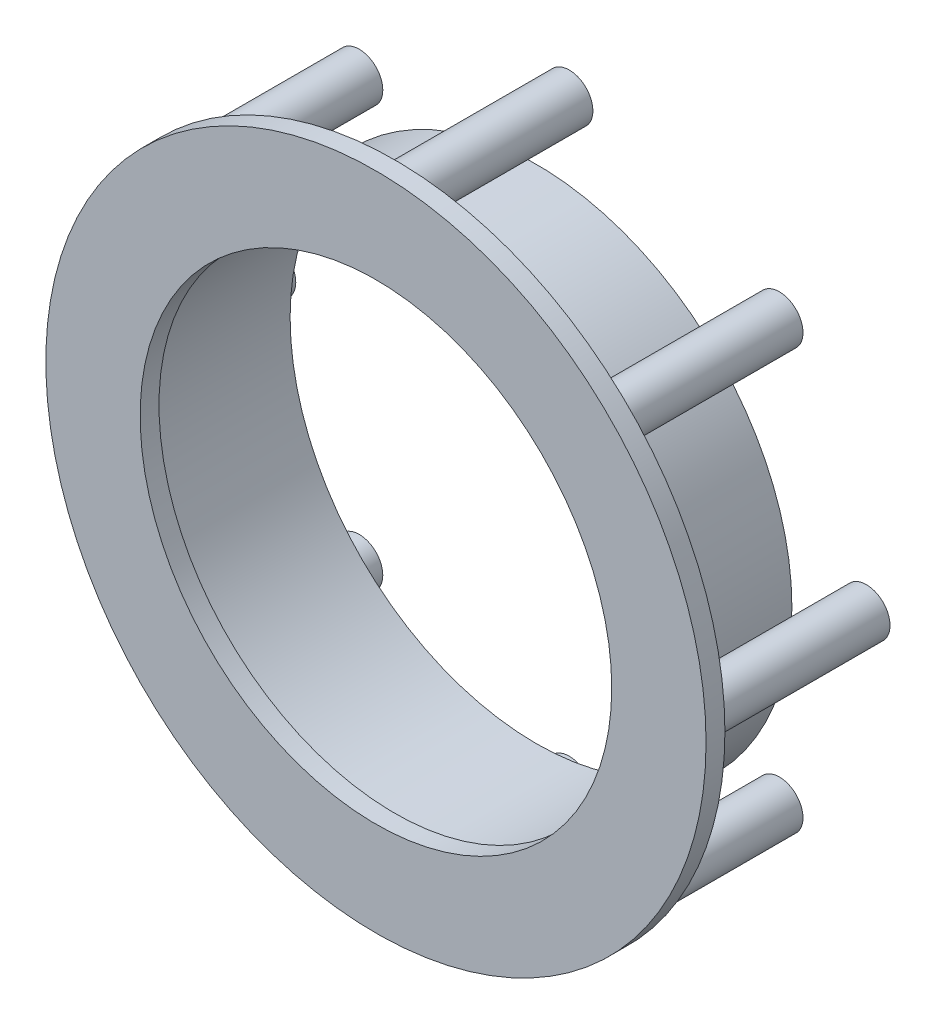
SolidWorks part; units mm, degrees
ref_plane "Alzado" through (0, 0, 0) normal (0, 0, 1) x (1, 0, 0)
ref_plane "Planta" through (0, 0, 0) normal (0, 1, 0) x (1, 0, 0)
ref_plane "Vista lateral" through (0, 0, 0) normal (1, 0, 0) x (0, 0, -1)
sketch "Croquis1" plane through (0, 0, 0) normal (0, 0, 1) x (1, 0, 0)
  circle A0 centre (0, 0) radius 35
  circle A1 centre (0, 0) radius 25
  dimension "D1" = 70
  dimension "D2" = 50
extrude "Saliente-Extruir1" add sketch "Croquis1" along normal blind 2
sketch "Croquis2" plane through (0, 0, 0) normal (0, 0, -1) x (-1, 0, 0)
  circle A0 centre (0, 0) radius 27.1
  circle A1 centre (0, 0) radius 26.1
  dimension "D1" = 54.2
  dimension "D2" = 52.2
extrude "Saliente-Extruir3" add sketch "Croquis2" along normal blind 15
sketch "Croquis5" plane through (0, 0, 0) normal (0, 0, -1) x (-1, 0, 0)
  line L0 (0, 0) -> (31.5, 0) construction
  circle A0 centre (31.5, 0) radius 2.5
  circle A1 centre (22.2739, -22.2739) radius 2.5
  circle A2 centre (0, -31.5) radius 2.5
  circle A3 centre (-22.2739, -22.2739) radius 2.5
  circle A4 centre (-31.5, 0) radius 2.5
  circle A5 centre (-22.2739, 22.2739) radius 2.5
  circle A6 centre (0, 31.5) radius 2.5
  circle A7 centre (22.2739, 22.2739) radius 2.5
  circle A9 centre (0, 0) radius 31.5 construction
  point P4 (0, 0)
  point P5 (0, 0)
  dimension "D1" = 5
  dimension "D2" = 31.5
  dimension "D3" = 8
extrude "Saliente-Extruir5" add sketch "Croquis5" along normal blind 18.5
